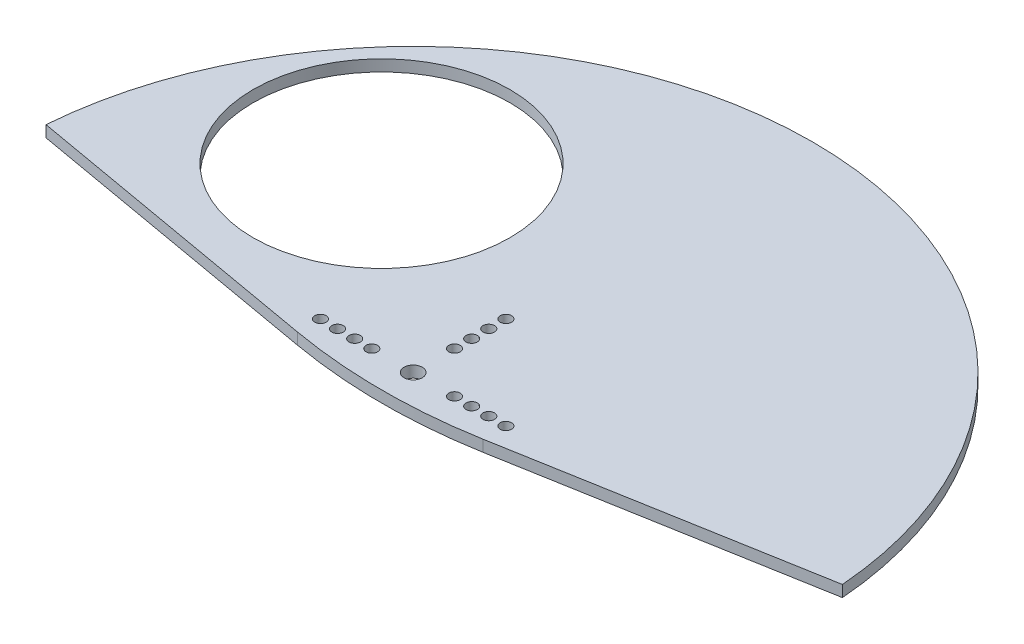
SolidWorks part; units mm, degrees
ref_plane "前基準面" through (0, 0, 0) normal (0, 0, 1) x (1, 0, 0)
ref_plane "上基準面" through (0, 0, 0) normal (0, 1, 0) x (1, 0, 0)
ref_plane "右基準面" through (0, 0, 0) normal (1, 0, 0) x (0, 0, -1)
sketch "草圖1" plane through (0, 0, 0) normal (0, 1, 0) x (1, 0, 0)
  line L0 (-69.7883, 5.4402) -> (-16.25, -4)
  line L1 (16.25, -4) -> (69.7883, 5.4402)
  line L2 (0, 16.25) -> (0, 0) construction
  line L3 (-16.25, 0) -> (0, 0) construction
  line L4 (16.25, 0) -> (0, 0) construction
  line L8 (-34.472, 28.9254) -> (0, 0) construction
  arc A0 (69.7883, 5.4402) -> (-69.7883, 5.4402) centre (0, 0) ccw
  circle A1 centre (16.25, 0) radius 1
  circle A2 centre (13.25, 0) radius 1
  circle A3 centre (10.25, 0) radius 1
  circle A4 centre (7.25, 0) radius 1
  circle A5 centre (-16.25, 0) radius 1
  circle A6 centre (-13.25, 0) radius 1
  circle A7 centre (-10.25, 0) radius 1
  circle A8 centre (-7.25, 0) radius 1
  circle A9 centre (0, 16.25) radius 1
  circle A10 centre (0, 13.25) radius 1
  circle A11 centre (0, 10.25) radius 1
  circle A12 centre (0, 7.25) radius 1
  circle A13 centre (0, 0) radius 1.6
  arc A14 (-16.25, -4) -> (16.25, -4) centre (0, 88.1583) ccw
  circle A15 centre (0, 0) radius 7.25 construction
  circle A20 centre (-34.472, 28.9254) radius 22.5
  dimension "D1" = 70
  dimension "D15" = 3.2
  dimension "D13" = 14.5
  dimension "D14" = 2
  dimension "D19" = 45
  dimension "D2" = 200
  dimension "D3" = 80
  dimension "D4" = 3
  dimension "D5" = 3
  dimension "D6" = 3
  dimension "D7" = 3
  dimension "D8" = 3
  dimension "D9" = 3
  dimension "D10" = 3
  dimension "D11" = 3
  dimension "D12" = 3
  dimension "D16" = 4
  dimension "D17" = 45
  dimension "D18" = 40
extrude "填料-伸長1" add sketch "草圖1" along normal mid plane 2 contours L0 A14 L1 A0 A1 A2 A3 A4 A5 A6 A7 A8 A9 A10 A11 A12 A13
